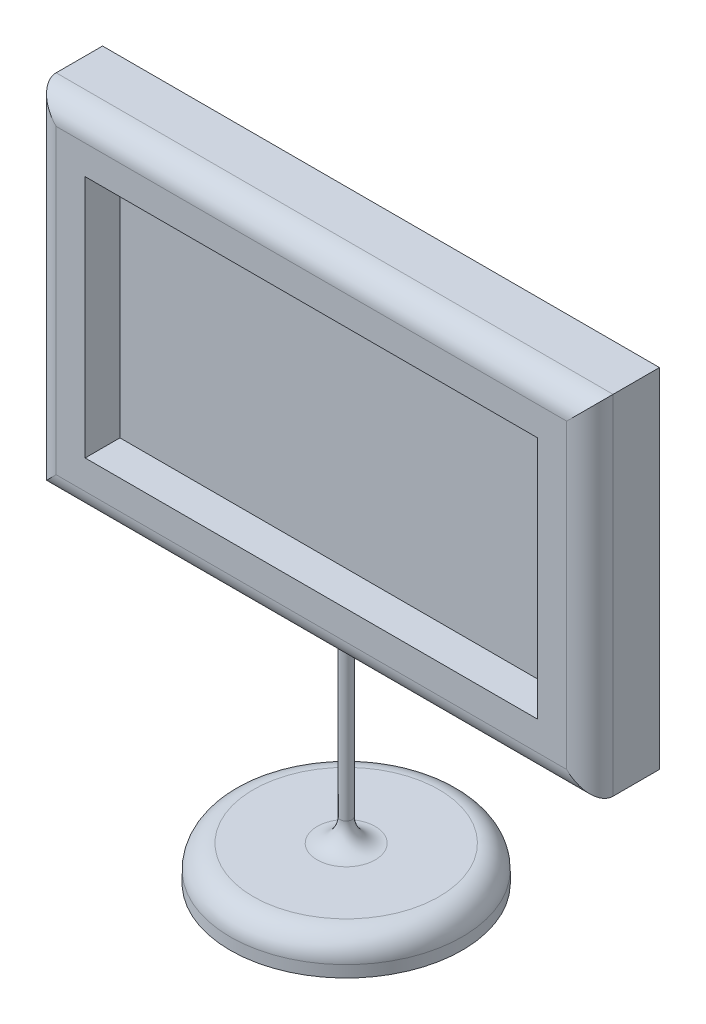
SolidWorks part; units mm, degrees
ref_plane "Front Plane" through (0, 0, 0) normal (0, 0, 1) x (1, 0, 0)
ref_plane "Top Plane" through (0, 0, 0) normal (0, 1, 0) x (1, 0, 0)
ref_plane "Right Plane" through (0, 0, 0) normal (1, 0, 0) x (0, 0, -1)
sketch "Sketch1" plane through (0, 0, 0) normal (0, 1, 0) x (1, 0, 0)
  circle A0 centre (0, 0) radius 50
  dimension "D1" = 100
extrude "Boss-Extrude1" add sketch "Sketch1" along normal blind 15
fillet "Fillet1" radius 10 1 edges at (0, 15, 50)
sketch "Sketch3" plane through (0, 0, 0) normal (0, 0, 1) x (1, 0, 0)
  line L0 (0, 0) -> (0, 10) construction
  line L1 (0, 0) -> (40, 0)
  line L2 (40, 0) -> (40, 5)
  line L3 (0, 10) -> (35, 10)
  line L4 (-50, 5) -> (50, 5) construction
  line L5 (0, 0) -> (0, 10)
  arc A0 (40, 5) -> (35, 10) centre (35, 5) ccw
  dimension "D2" = 5
  dimension "D1" = 10
  dimension "D3" = 40
revolve "Cut-Revolve1" cut sketch "Sketch3" angle 360 about L0
sketch "Sketch5" plane through (0, 15, 0) normal (0, 1, 0) x (1, 0, 0)
  circle A0 centre (0, 0) radius 2.5
  dimension "D1" = 5
extrude "Boss-Extrude2" add sketch "Sketch5" along normal blind 80
fillet "Fillet2" radius 10 1 edges at (0, 15, 2.5)
sketch "Sketch6" plane through (0, 0, 0) normal (0, 0, 1) x (1, 0, 0)
  line L1 (-120, 245) -> (120, 245)
  line L2 (-120, 245) -> (-120, 95)
  line L3 (-120, 95) -> (120, 95)
  line L4 (120, 245) -> (120, 95)
  line L5 (2.5, 95) -> (-2.5, 95) construction
  point P7 (0, 95)
  dimension "D1" = 240
  dimension "D2" = 150
extrude "Boss-Extrude3" add sketch "Sketch6" along normal mid plane 30
sketch "Sketch7" plane through (0, 0, 15) normal (0, 0, 1) x (1, 0, 0)
  line L0 (-120, 245) -> (-120, 95) construction
  line L1 (-97.5, 222.5) -> (97.5, 222.5)
  line L2 (-97.5, 222.5) -> (-97.5, 117.5)
  line L3 (-97.5, 117.5) -> (97.5, 117.5)
  line L4 (97.5, 222.5) -> (97.5, 117.5)
  point P4 (0, 222.5)
  point P6 (-97.5, 170)
  point P9 (-120, 170)
  dimension "D1" = 105
  dimension "D2" = 195
extrude "Cut-Extrude1" cut sketch "Sketch7" against normal blind 15
fillet "Fillet3" radius 10 4 edges at (0, 95, 15) (-120, 170, 15) (0, 245, 15) (120, 170, 15)
